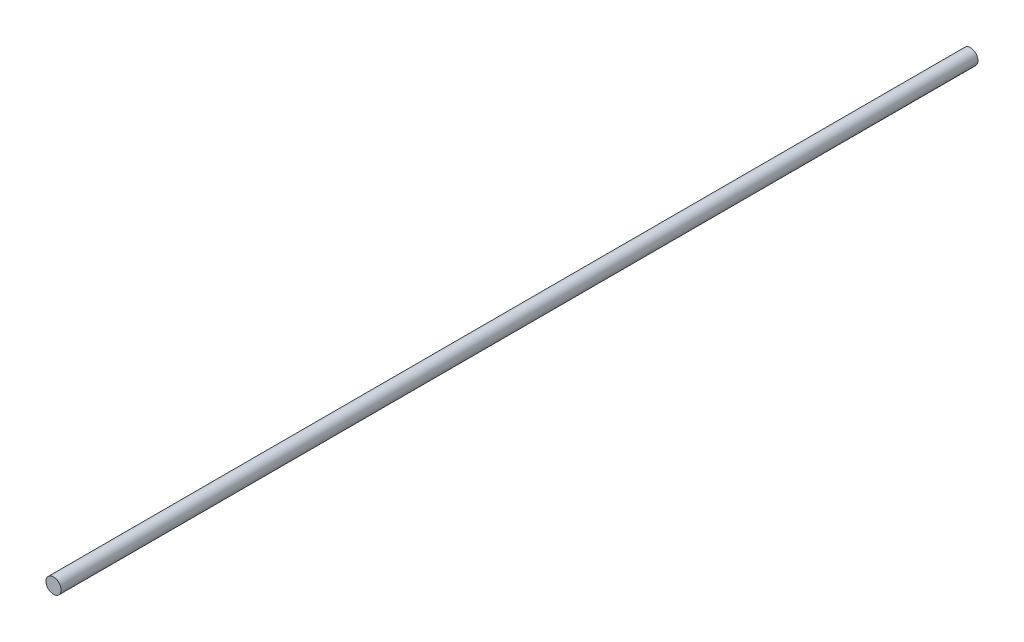
SolidWorks part; units mm, degrees
material "Zero density"
ref_plane "Piano frontale" through (0, 0, 0) normal (0, 0, 1) x (1, 0, 0)
ref_plane "Piano superiore" through (0, 0, 0) normal (0, 1, 0) x (1, 0, 0)
ref_plane "Piano destro" through (0, 0, 0) normal (1, 0, 0) x (0, 0, -1)
sketch "Schizzo1" plane through (0, 0, 0) normal (0, 0, 1) x (1, 0, 0)
  circle A0 centre (0, 0) radius 1.5
  dimension "D1" = 3
extrude "Estrusione-Estrusione1" add sketch "Schizzo1" along normal blind 182
